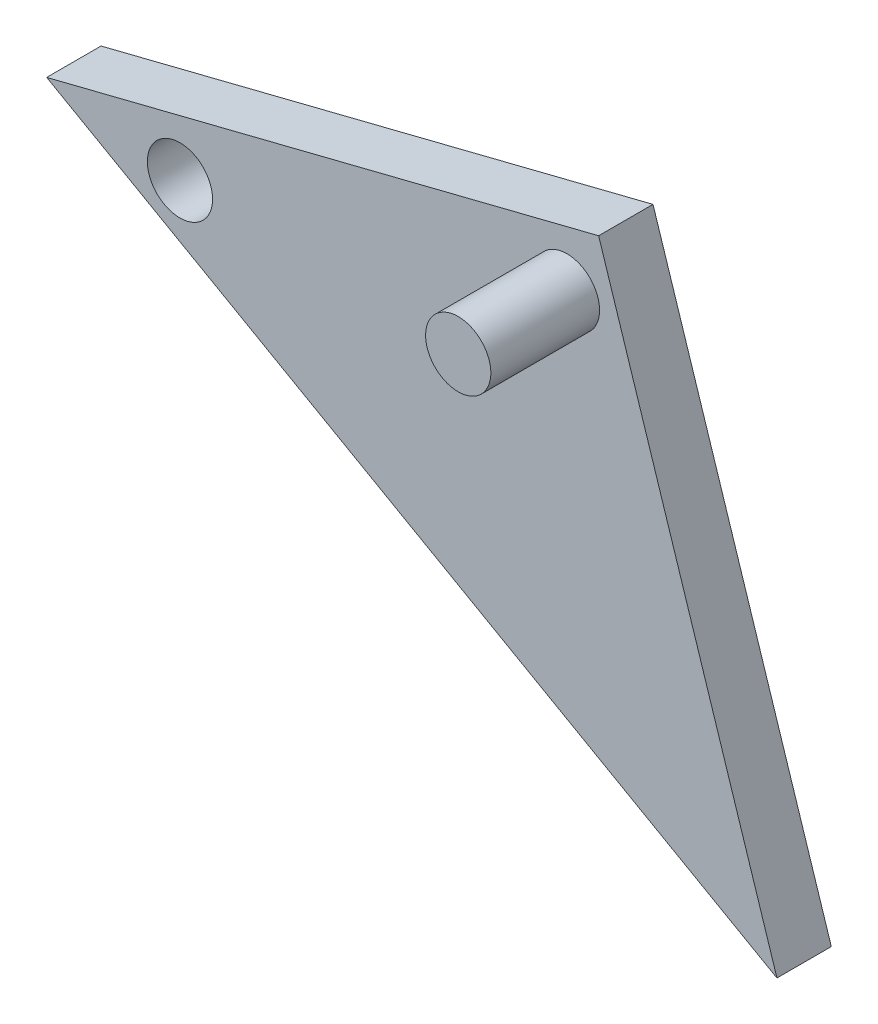
SolidWorks part; units mm, degrees
ref_plane "Front Plane" through (0, 0, 0) normal (0, 0, 1) x (1, 0, 0)
ref_plane "Top Plane" through (0, 0, 0) normal (0, 1, 0) x (1, 0, 0)
ref_plane "Right Plane" through (0, 0, 0) normal (1, 0, 0) x (0, 0, -1)
sketch "Sketch1" plane through (0, 0, 0) normal (0, 0, 1) x (1, 0, 0)
  line L3 (-12.2584, 2.0723) -> (38.5059, 14.8415)
  line L8 (38.5059, 14.8415) -> (54.9067, -36.0798)
  line L9 (54.9067, -36.0798) -> (-12.2584, 2.0723)
  circle A0 centre (0, 0) radius 3
  circle A1 centre (35.5913, 8.9526) radius 3
  dimension "D5" = 6
  dimension "D6" = 6
  dimension "D1" = 36.7
  dimension "D2" = 49
  dimension "D3" = 65.7
extrude "Boss-Extrude1" add sketch "Sketch1" along normal blind 5
sketch "Sketch2" plane through (0, 0, 0) normal (0, 0, -1) x (-1, 0, 0)
  circle A0 centre (-35.5913, 8.9526) radius 3
extrude "Boss-Extrude2" add sketch "Sketch2" against normal blind 15
